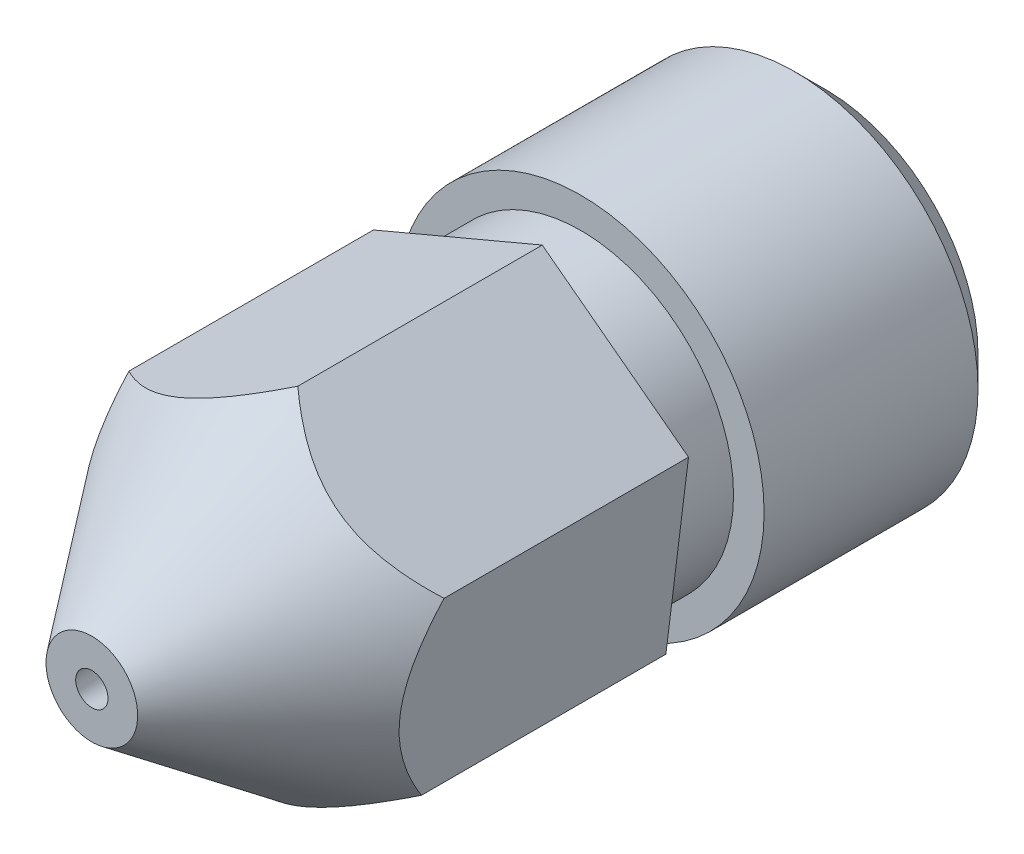
SolidWorks part; units mm, degrees
material "Latón de decoletaje, UNS C36000"
ref_plane "Alzado" through (0, 0, 0) normal (0, 0, 1) x (1, 0, 0)
ref_plane "Planta" through (0, 0, 0) normal (0, 1, 0) x (1, 0, 0)
ref_plane "Vista lateral" through (0, 0, 0) normal (1, 0, 0) x (0, 0, -1)
sketch "Croquis1" plane through (0, 0, 0) normal (0, 1, 0) x (1, 0, 0)
  line L0 (2.5, 5) -> (0, 5)
  line L1 (0, 5) -> (0, 0)
  line L2 (0, 0) -> (2.5, 0)
  line L3 (2.5, 0) -> (2.5, 1)
  line L4 (2.5, 1) -> (3, 1)
  line L5 (3, 1) -> (3, 4.5)
  line L6 (3, 4.5) -> (2.5, 5)
  line L7 (0, 5) -> (0, 0) construction
revolve "Revolución1" add sketch "Croquis1" angle 360 about L7
sketch "Croquis2" plane through (0, 0, 0) normal (0, 1, 0) x (1, 0, 0)
  line L0 (1.5, 5) -> (0, 5)
  line L1 (0, 5) -> (0, -8)
  line L2 (0, -8) -> (0.2, -8)
  line L3 (0.2, -8) -> (0.2, -7.2)
  line L4 (0.2, -7.2) -> (1, -6.4)
  line L5 (1, -6.4) -> (1, 4.5)
  line L6 (1, 4.5) -> (1.5, 5)
  line L7 (0, 5) -> (0, -8) construction
revolve "Cortar-Revolución1" cut sketch "Croquis2" angle 360 about L7
ref_plane "Plano1" through (0, 0, 0) normal (0, 0, 1) x (1, 0, 0)
ref_plane "Plano2" through (0, 0, 7) normal (0, 0, 1) x (1, 0, 0)
sketch "Croquis4" plane through (0, 0, 0) normal (0, 1, 0) x (1, 0, 0)
  line L0 (0, 0) -> (0, -8)
  line L2 (0, -8) -> (3, -4)
  line L3 (0, 0) -> (3, 0)
  line L4 (-2.75, 0) -> (2.75, 0) construction
  line L5 (3, 0) -> (3, -4)
  point P3 (0, 0)
  dimension "D1" = 8
  dimension "D2" = 4
revolve "Revolución2" add sketch "Croquis4" angle 360 about L0
sketch "Croquis8" plane through (0, 0, 7) normal (0, 0, 1) x (1, 0, 0)
  line L1 (-1.1396, -1.1042) -> (1.0353, -1.1042)
  line L2 (-1.1396, -1.1042) -> (-1.1396, 1.0886)
  line L3 (-1.1396, 1.0886) -> (1.0353, 1.0886)
  line L4 (1.0353, -1.1042) -> (1.0353, 1.0886)
extrude "Cortar-Extruir2" cut sketch "Croquis8" along normal blind 10
sketch "Croquis10" plane through (0, 0, 7) normal (0, 0, 1) x (1, 0, 0)
  circle A1 centre (0, 0) radius 0.2
  dimension "D1" = 0.4
sketch "Croquis11" plane through (0, 0, 0) normal (0, 0, 1) x (1, 0, 0)
  circle A2 centre (0, 0) radius 1
extrude "Cortar-Extruir3" cut sketch "Croquis11" along normal through all draft 6 contours A2
sketch "Croquis13" plane through (0, 0, 0) normal (0, 0, 1) x (1, 0, 0)
  line L1 (2.7634, 1.1678) -> (0.3704, 2.977)
  line L2 (0.3704, 2.977) -> (-2.393, 1.8093)
  line L3 (-2.393, 1.8093) -> (-2.7634, -1.1678)
  line L4 (-2.7634, -1.1678) -> (-0.3704, -2.977)
  line L5 (-0.3704, -2.977) -> (2.393, -1.8093)
  line L6 (2.393, -1.8093) -> (2.7634, 1.1678)
  circle A0 centre (0, 0) radius 2.5981 construction
extrude "Cortar-Extruir4" cut sketch "Croquis13" along normal blind 10 flip side to cut
